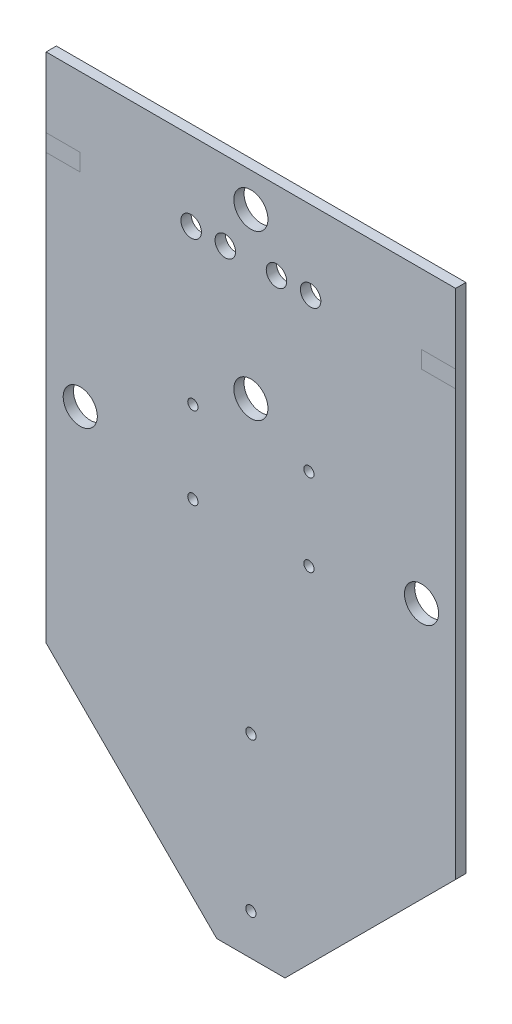
SolidWorks part; units mm, degrees
ref_plane "Plan de face" through (0, 0, 0) normal (0, 0, 1) x (1, 0, 0)
ref_plane "Plan de dessus" through (0, 0, 0) normal (0, 1, 0) x (1, 0, 0)
ref_plane "Plan de droite" through (0, 0, 0) normal (1, 0, 0) x (0, 0, -1)
sketch "Esquisse1" plane through (0, 0, 0) normal (0, 0, 1) x (1, 0, 0)
  line L0 (0, 0) -> (-120, 0)
  line L1 (-120, 0) -> (-120, -150)
  line L2 (-120, -150) -> (-70, -200)
  line L3 (-70, -200) -> (-50, -200)
  line L4 (-50, -200) -> (0, -150)
  line L5 (0, -150) -> (0, 0)
  dimension "D1" = 120
  dimension "D2" = 150
  dimension "D3" = 50
  dimension "D4" = 135
  dimension "D5" = 150
  dimension "D6" = 135
extrude "Extrusion1" add sketch "Esquisse1" along normal blind 3
sketch "Esquisse4" plane through (0, 0, 0) normal (0, 0, -1) x (-1, 0, 0)
  line L0 (120, 0) -> (0, -20) construction
  line L1 (0, -150) -> (20, -20) construction
  line L2 (100, -20) -> (120, -150) construction
  line L3 (0, -150) -> (0, 0) construction
  line L6 (0, 0) -> (120, 0) construction
  circle A0 centre (60, -10) radius 5
  circle A1 centre (10, -85) radius 5
  circle A2 centre (110, -85) radius 5
  dimension "D1" = 10
  dimension "D2" = 10
  dimension "D3" = 10
  dimension "D4" = 60
  dimension "D5" = 20
  dimension "D6" = 20
  dimension "D7" = 10
extrude "Enlèv. mat.-Extru.3" cut sketch "Esquisse4" against normal blind 16
sketch "Esquisse8" plane through (0, 0, 0) normal (0, 0, -1) x (-1, 0, 0)
  line L0 (42.5, -23) -> (56.115, -23) construction
  line L1 (60, 0) -> (60, -30.4584) construction
  line L2 (0, 0) -> (120, 0) construction
  circle A0 centre (52.5, -23) radius 3
  circle A1 centre (42.5, -23) radius 3
  circle A2 centre (67.5, -23) radius 3
  circle A3 centre (77.5, -23) radius 3
  dimension "D1" = 6
  dimension "D2" = 6
  dimension "D5" = 23
  dimension "D3" = 10
  dimension "D4" = 7.5
extrude "Enlèv. mat.-Extru.5" cut sketch "Esquisse8" against normal blind 8
sketch "Esquisse9" plane through (0, 0, 0) normal (0, 0, -1) x (-1, 0, 0)
  line L0 (60, -200) -> (60, -125.641) construction
  line L1 (70, -200) -> (50, -200) construction
  circle A0 centre (60, -143) radius 1.5
  circle A1 centre (60, -188) radius 1.5
  dimension "D2" = 3
  dimension "D3" = 3
  dimension "D1" = 45
  dimension "D4" = 12
extrude "Enlèv. mat.-Extru.6" cut sketch "Esquisse9" against normal blind 10
sketch "Esquisse11" plane through (0, 0, 3) normal (0, 0, 1) x (1, 0, 0)
  line L0 (-60, 0) -> (-60, -34.3167) construction
  line L1 (0, 0) -> (-120, 0) construction
  line L2 (-120, -20.5) -> (-110, -20.5)
  line L3 (-120, -20.5) -> (-120, -25.5)
  line L4 (-120, -25.5) -> (-110, -25.5)
  line L5 (-110, -20.5) -> (-110, -25.5)
  line L6 (-60, -23) -> (-92.2821, -23) construction
  line L7 (-92.2821, -23) -> (-110, -23) construction
  line L8 (-120, 0) -> (-120, -150) construction
  line L9 (-10, -20.5) -> (-10, -25.5)
  line L10 (0, -20.5) -> (0, -25.5)
  line L11 (0, -20.5) -> (-10, -20.5)
  line L12 (0, -25.5) -> (-10, -25.5)
  dimension "D1" = 10
  dimension "D2" = 23
  dimension "D3" = 5
extrude "Enlèv. mat.-Extru.9" cut sketch "Esquisse11" against normal blind 0.0001
sketch "Esquisse12" plane through (0, 0, 0) normal (0, 0, -1) x (-1, 0, 0)
  line L0 (30, -133.9947) -> (30, -137)
  line L1 (30, -137) -> (31.8596, -137)
  line L2 (31.8596, -137) -> (31.8596, -139)
  line L3 (31.8596, -139) -> (28, -139)
  line L4 (28, -139) -> (28, -133.9947)
  line L5 (28, -133.9947) -> (30, -133.9947)
  line L6 (0, -150) -> (0, 0) construction
  circle A0 centre (60, -143) radius 1.5 construction
  dimension "D1" = 30
  dimension "D2" = 2
  dimension "D3" = 2
  dimension "D4" = 6
extrude "Extrusion2" add sketch "Esquisse12" along normal blind 2
sketch "Esquisse5" plane through (0, 0, 0) normal (0, 0, 1) x (1, 0, 0)
  line L1 (-31.8596, -137) -> (-30, -137) construction
  line L2 (-77, -68) -> (-43, -68) construction
  line L3 (-43, -68) -> (-43, -92) construction
  line L4 (-43, -92) -> (-77, -92) construction
  line L5 (-77, -92) -> (-77, -68) construction
  line L8 (-60, -92) -> (-60, -97.9208) construction
  line L9 (0, -150) -> (0, 0) construction
  circle A0 centre (-77, -68) radius 1.5
  circle A1 centre (-43, -68) radius 1.5
  circle A2 centre (-43, -92) radius 1.5
  circle A3 centre (-77, -92) radius 1.5
  dimension "D1" = 3
  dimension "D2" = 3
  dimension "D3" = 3
  dimension "D4" = 3
  dimension "D5" = 45
  dimension "D6" = 60
  dimension "D7" = 34
  dimension "D8" = 24
extrude "Enlèv. mat.-Extru.4" cut sketch "Esquisse5" along normal blind 25.7922
sketch "Esquisse3" plane through (0, 0, 0) normal (0, 0, -1) x (-1, 0, 0)
  line L0 (0, -150) -> (0, 0) construction
  circle A0 centre (60, -58) radius 5
  circle A1 centre (43, -68) radius 1.5 construction
  dimension "D1" = 10
  dimension "D2" = 60
  dimension "D3" = 10
extrude "Enlèv. mat.-Extru.2" cut sketch "Esquisse3" against normal blind 16
